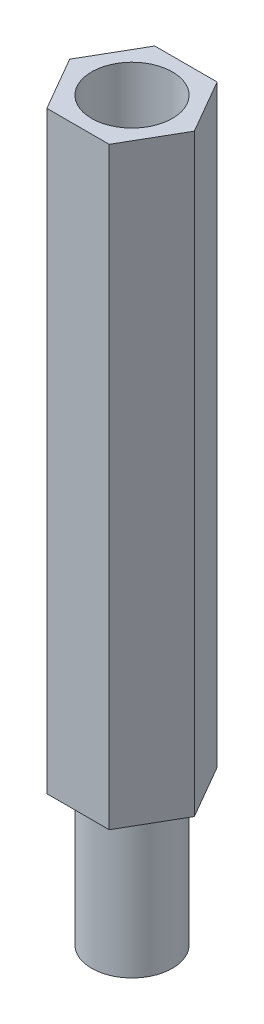
SolidWorks part; units mm, degrees
ref_plane "前视基准面" through (0, 0, 0) normal (0, 0, 1) x (1, 0, 0)
ref_plane "上视基准面" through (0, 0, 0) normal (0, 1, 0) x (1, 0, 0)
ref_plane "右视基准面" through (0, 0, 0) normal (1, 0, 0) x (0, 0, -1)
sketch "草图1" plane through (0, 0, 0) normal (0, 1, 0) x (1, 0, 0)
  line L2 (1.3125, -2.2733) -> (2.625, 0)
  line L4 (1.3125, 2.2733) -> (-1.3125, 2.2733)
  line L5 (-1.3125, 2.2733) -> (-2.625, 0)
  line L6 (1.3125, 2.2733) -> (2.625, 0)
  line L7 (1.3125, -2.2733) -> (-1.3125, -2.2733)
  line L8 (-1.3125, -2.2733) -> (-2.625, 0)
extrude "凸台-拉伸1" add sketch "草图1" along normal blind 25
sketch "草图2" plane through (0, 0, 0) normal (0, 1, 0) x (1, 0, 0)
  circle A0 centre (0, 0) radius 1.7
extrude "凸台-拉伸2" add sketch "草图2" against normal blind 6
sketch "草图3" plane through (0, 25, 0) normal (0, 1, 0) x (1, 0, 0)
  circle A0 centre (0, 0) radius 1.7
extrude "切除-拉伸1" cut sketch "草图3" against normal blind 4
